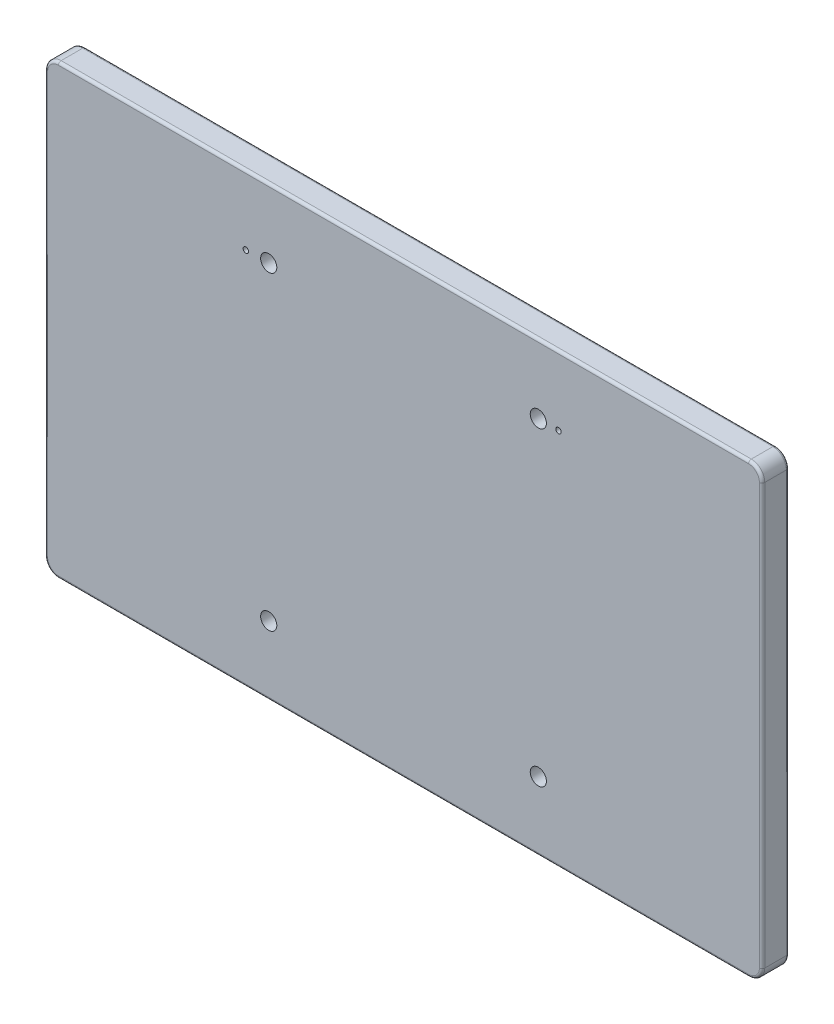
SolidWorks part; units mm, degrees
material "PP Copolymer"
ref_plane "Front Plane" through (0, 0, 0) normal (0, 0, 1) x (1, 0, 0)
ref_plane "Top Plane" through (0, 0, 0) normal (0, 1, 0) x (1, 0, 0)
ref_plane "Right Plane" through (0, 0, 0) normal (1, 0, 0) x (0, 0, -1)
sketch "Sketch1" plane through (0, 0, 0) normal (0, 0, 1) x (1, 0, 0)
  line L0 (-116, 150) -> (116, 150) construction
  line L1 (-125, 158) -> (125, 158)
  line L2 (-133, 150) -> (-133, 0)
  line L3 (-125, -8) -> (125, -8)
  line L4 (133, 150) -> (133, 0)
  line L5 (-133, 158) -> (133, -8) construction
  line L6 (-133, -8) -> (133, 158) construction
  line L7 (-125, 10) -> (-125, 149) construction
  line L8 (115, 0) -> (-115, 0) construction
  line L9 (125, 149) -> (125, 10) construction
  line L11 (133, 158) -> (-133, 158)
  line L12 (133, 158) -> (133, -8)
  line L13 (133, -8) -> (-133, -8)
  line L14 (-133, 158) -> (-133, -8)
  line L15 (133, 158) -> (-133, -8) construction
  line L16 (133, -8) -> (-133, 158) construction
  point P0 (0, 75)
  point P25 (0, 75)
  dimension "D1" = 8
  dimension "D2" = 8
  dimension "D3" = 8
  dimension "D4" = 8
extrude "Boss-Extrude1" add sketch "Sketch1" along normal blind 10 contours L11 L14 L2 L13 L3 L12 L4 L1
fillet "Fillet1" radius 5
sketch "Sketch2" plane through (0, 0, 0) normal (0, 0, -1) x (-1, 0, 0)
  circle A0 centre (-50, 132.5) radius 3
  circle A1 centre (50, 132.5) radius 3
  circle A2 centre (-50, 17.5) radius 3
  circle A3 centre (50, 17.5) radius 3
  dimension "D1" = 6
extrude "Cut-Extrude1" cut sketch "Sketch2" along normal through all both and the other way through all
fillet "Fillet2" radius 1
sketch "Sketch3" [suppressed] plane through (0, 0, 0) normal (0, 0, -1) x (-1, 0, 0)
  line L1 (-105, 117.5) -> (105, 117.5)
  line L2 (-105, 117.5) -> (-105, 25)
  line L3 (-105, 25) -> (105, 25)
  line L4 (105, 117.5) -> (105, 25)
  line L5 (-105, 117.5) -> (105, 25) construction
  line L6 (-105, 25) -> (105, 117.5) construction
  point P0 (0, 71.25)
sketch "Sketch4" plane through (0, 0, 0) normal (0, 0, -1) x (-1, 0, 0)
  circle A0 centre (58.5, 132.4) radius 1
  circle A1 centre (-57.5, 132.4) radius 1
  circle A2 centre (50, 132.5) radius 2 construction
  dimension "D1" = 2
  dimension "D4" = 0.1
  dimension "D2" = 116
  dimension "D3" = 8.5
extrude "Cut-Extrude2" cut sketch "Sketch4" against normal through all
